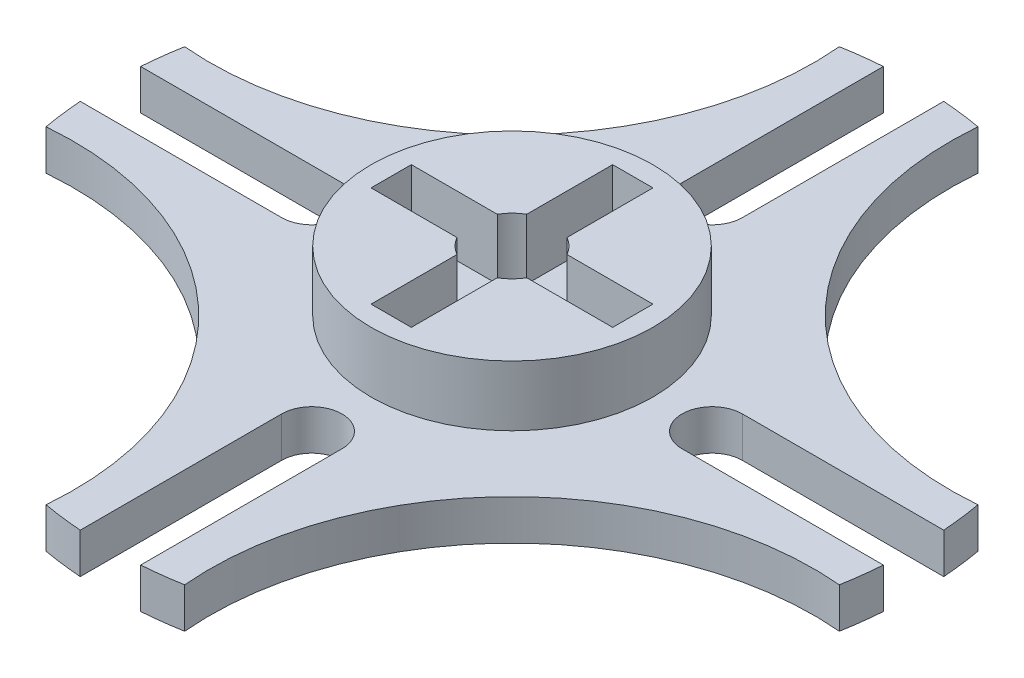
SolidWorks part; units mm, degrees
ref_plane "Front Plane" through (0, 0, 0) normal (0, 0, 1) x (1, 0, 0)
ref_plane "Top Plane" through (0, 0, 0) normal (0, 1, 0) x (1, 0, 0)
ref_plane "Right Plane" through (0, 0, 0) normal (1, 0, 0) x (0, 0, -1)
sketch "Sketch1" plane through (0, 0, 0) normal (0, 1, 0) x (1, 0, 0)
  line L0 (0, 35) -> (0, 100) construction
  line L1 (-7.5, 49.7184) -> (-7.5, 99.7184)
  line L2 (7.5, 49.7184) -> (7.5, 99.7184)
  line L3 (49.7184, 7.5) -> (99.7184, 7.5)
  line L4 (49.7184, -7.5) -> (99.7184, -7.5)
  line L5 (7.5, -49.7184) -> (7.5, -99.7184)
  line L6 (-7.5, -49.7184) -> (-7.5, -99.7184)
  line L7 (-49.7184, -7.5) -> (-99.7184, -7.5)
  line L8 (-49.7184, 7.5) -> (-99.7184, 7.5)
  line L9 (0, 0) -> (-38.8909, 38.8909) construction
  line L10 (-70.7107, 70.7107) -> (-91.9239, 91.9239) construction
  arc A0 (-7.5, 99.7184) -> (-17.2134, 98.5074) centre (0, 0) ccw
  arc A1 (-7.5, 49.7184) -> (7.5, 49.7184) centre (0, 49.7184) ccw
  arc A4 (49.7184, 7.5) -> (49.7184, -7.5) centre (49.7184, 0) ccw
  arc A6 (7.5, -49.7184) -> (-7.5, -49.7184) centre (0, -49.7184) ccw
  arc A8 (-49.7184, -7.5) -> (-49.7184, 7.5) centre (-49.7184, 0) ccw
  arc A9 (-99.7184, -7.5) -> (-98.5074, -17.2134) centre (0, 0) ccw
  arc A10 (99.7184, 7.5) -> (98.5074, 17.2134) centre (0, 0) ccw
  arc A11 (7.5, -99.7184) -> (17.2134, -98.5074) centre (0, 0) ccw
  arc A12 (-98.5074, 17.2134) -> (-17.2134, 98.5074) centre (-91.9239, 91.9239) ccw
  arc A13 (-98.5074, 17.2134) -> (-99.7184, 7.5) centre (0, 0) ccw
  arc A15 (17.2134, 98.5074) -> (98.5074, 17.2134) centre (91.9239, 91.9239) ccw
  arc A17 (98.5074, -17.2134) -> (17.2134, -98.5074) centre (91.9239, -91.9239) ccw
  arc A19 (-17.2134, -98.5074) -> (-98.5074, -17.2134) centre (-91.9239, -91.9239) ccw
  arc A20 (17.2134, 98.5074) -> (7.5, 99.7184) centre (0, 0) ccw
  arc A21 (98.5074, -17.2134) -> (99.7184, -7.5) centre (0, 0) ccw
  arc A22 (-17.2134, -98.5074) -> (-7.5, -99.7184) centre (0, 0) ccw
  point P30 (0, 0)
  point P48 (0, 0)
  dimension "D1" = 200
  dimension "D2" = 15
  dimension "D6" = 150
  dimension "D3" = 50
  dimension "D5" = 45
  dimension "D7" = 130
  dimension "D8" = 4
  dimension "D4" = 4
extrude "Boss-Extrude3" add sketch "Sketch1" along normal blind 10
sketch "Sketch2" plane through (0, 10, 0) normal (0, 1, 0) x (1, 0, 0)
  line L0 (0, 35) -> (0, -35) construction
  line L1 (-5, 30) -> (5, 30)
  line L2 (-5, 30) -> (-5, -30)
  line L3 (-5, -30) -> (5, -30)
  line L4 (5, 30) -> (5, -30)
  line L5 (-30, 5) -> (30, 5)
  line L6 (-30, 5) -> (-30, -5)
  line L7 (-30, -5) -> (30, -5)
  line L8 (30, 5) -> (30, -5)
  line L9 (-35, 0) -> (35, 0) construction
  circle A0 centre (0, 0) radius 35
  circle A1 centre (0, 0) radius 10
  dimension "D1" = 70
  dimension "D2" = 20
  dimension "D3" = 60
  dimension "D4" = 30
  dimension "D5" = 10
  dimension "D6" = 5
  dimension "D7" = 30
  dimension "D8" = 5
extrude "Boss-Extrude4" add sketch "Sketch2" along normal blind 15 contours A0 A1 L4 L3 L2 L7 L6 L5 L1 L8
